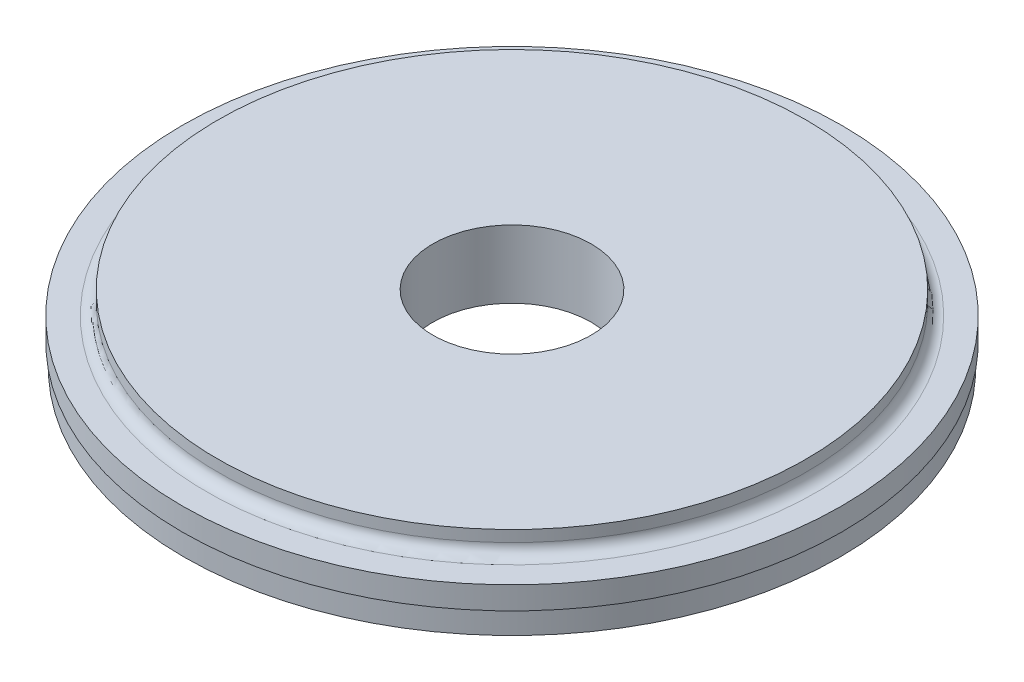
SolidWorks part; units mm, degrees
material "延性铁"
ref_plane "前视基准面" through (0, 0, 0) normal (0, 0, 1) x (1, 0, 0)
ref_plane "上视基准面" through (0, 0, 0) normal (0, 1, 0) x (1, 0, 0)
ref_plane "右视基准面" through (0, 0, 0) normal (1, 0, 0) x (0, 0, -1)
sketch "草图1" plane through (0, 0, 0) normal (1, 0, 0) x (0, 0, -1)
  line L0 (0, 0) -> (0, 38.8583) construction
  line L1 (-17.5, 15) -> (-17.5, 0)
  line L2 (-17.5, 0) -> (-72.5, 0)
  line L3 (-72.5, 0) -> (-72.5, 5)
  line L4 (-72.5, 5) -> (-72.9, 5)
  line L5 (-72.9, 5) -> (-72.9, 10)
  line L6 (-72.9, 10) -> (-67.5, 10)
  line L7 (-65, 12.5) -> (-65, 15)
  line L8 (-65, 15) -> (-17.5, 15)
  arc A0 (-67.5, 10) -> (-65, 12.5) centre (-67.5, 12.5) ccw
  point P13 (-65, 10)
  dimension "D8" = 2.5
  dimension "D1" = 35
  dimension "D2" = 145.8
  dimension "D3" = 145
  dimension "D4" = 130
  dimension "D5" = 5
  dimension "D6" = 5
  dimension "D7" = 15
revolve "旋转1" add sketch "草图1" angle 360 about L0
